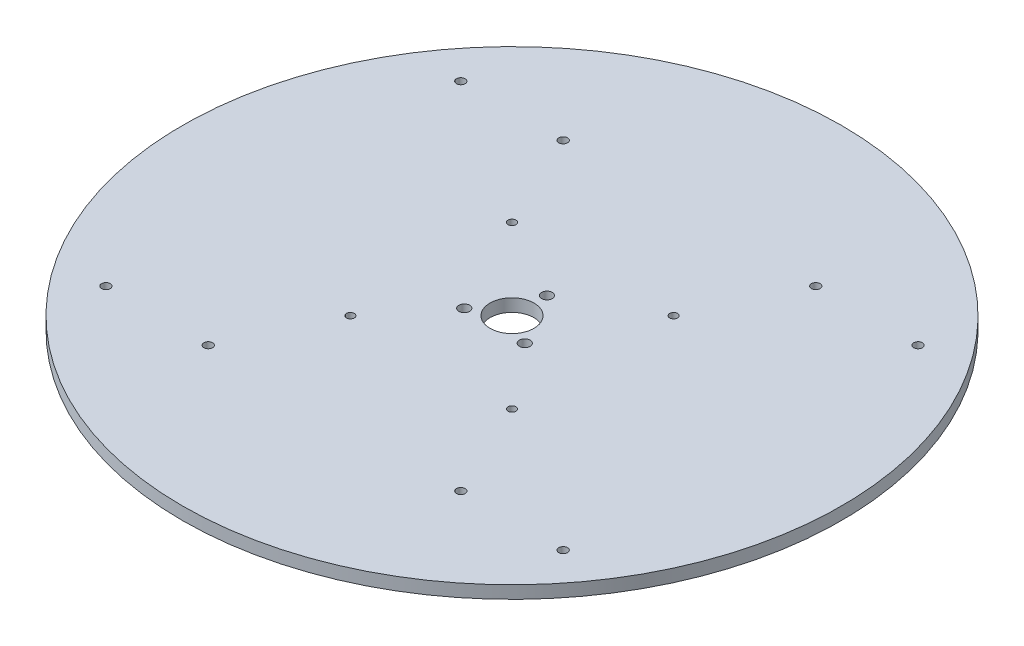
SolidWorks part; units mm, degrees
ref_plane "Front Plane" through (0, 0, 0) normal (0, 0, 1) x (1, 0, 0)
ref_plane "Top Plane" through (0, 0, 0) normal (0, 1, 0) x (1, 0, 0)
ref_plane "Right Plane" through (0, 0, 0) normal (1, 0, 0) x (0, 0, -1)
sketch "Sketch1" plane through (0, 0, 0) normal (0, 1, 0) x (1, 0, 0)
  circle A0 centre (0, 0) radius 165.1
  dimension "D1" = 330.2
extrude "Boss-Extrude1" add sketch "Sketch1" along normal blind 6.35
sketch "Sketch2" plane through (0, 6.35, 0) normal (0, 1, 0) x (1, 0, 0)
  line L0 (0, 0) -> (0, 17.5) construction
  line L1 (-40.4876, 40.4876) -> (40.4876, 40.4876) construction
  line L2 (-40.4876, 40.4876) -> (-40.4876, -40.4876) construction
  line L3 (-40.4876, -40.4876) -> (40.4876, -40.4876) construction
  line L4 (40.4876, 40.4876) -> (40.4876, -40.4876) construction
  line L5 (-40.4876, 40.4876) -> (40.4876, -40.4876) construction
  line L6 (-40.4876, -40.4876) -> (40.4876, 40.4876) construction
  line L7 (0, 0) -> (-15.1554, -8.75) construction
  line L8 (0, 0) -> (15.1554, -8.75) construction
  circle A0 centre (0, 0) radius 11
  circle A1 centre (-40.4876, 40.4876) radius 1.9844
  circle A2 centre (-40.4876, -40.4876) radius 1.9844
  circle A3 centre (40.4876, -40.4876) radius 1.9844
  circle A4 centre (40.4876, 40.4876) radius 1.9844
  circle A5 centre (0, 0) radius 17.5 construction
  circle A6 centre (0, 17.5) radius 2.7
  circle A7 centre (-15.1554, -8.75) radius 2.7
  circle A8 centre (15.1554, -8.75) radius 2.7
  dimension "D1" = 22
  dimension "D4" = 3.9688
  dimension "D5" = 35
  dimension "D8" = 5.4
  dimension "D2" = 80.9752
  dimension "D3" = 80.9752
  dimension "D6" = 120
  dimension "D7" = 120
extrude "Cut-Extrude1" cut sketch "Sketch2" against normal through all
sketch "Sketch3" plane through (0, 6.35, 0) normal (0, 1, 0) x (1, 0, 0)
  line L0 (-114.5413, 88.9) -> (-63.2587, 88.9) construction
  line L1 (-88.9, -88.9) -> (88.9, -88.9) construction
  line L2 (-88.9, -88.9) -> (-88.9, 88.9) construction
  line L3 (-88.9, 88.9) -> (88.9, 88.9) construction
  line L4 (88.9, -88.9) -> (88.9, 88.9) construction
  line L5 (-88.9, -88.9) -> (88.9, 88.9) construction
  line L6 (-88.9, 88.9) -> (88.9, -88.9) construction
  line L7 (-114.5413, -88.9) -> (-63.2587, -88.9) construction
  line L8 (114.5413, 88.9) -> (63.2587, 88.9) construction
  line L9 (114.5413, -88.9) -> (63.2587, -88.9) construction
  circle A0 centre (-114.5413, 88.9) radius 2.1828
  circle A1 centre (-63.2587, 88.9) radius 2.1828
  circle A2 centre (63.2587, 88.9) radius 2.1828
  circle A3 centre (114.5413, 88.9) radius 2.1828
  circle A4 centre (114.5413, -88.9) radius 2.1828
  circle A5 centre (63.2587, -88.9) radius 2.1828
  circle A6 centre (-63.2587, -88.9) radius 2.1828
  circle A7 centre (-114.5413, -88.9) radius 2.1828
  point P0 (0, 0)
  point P9 (-88.9, 88.9)
  point P12 (-88.9, -88.9)
  point P15 (88.9, 88.9)
  point P18 (88.9, -88.9)
  dimension "D1" = 4.3656
  dimension "D2" = 51.2826
  dimension "D3" = 177.8
  dimension "D4" = 177.8
extrude "Cut-Extrude2" cut sketch "Sketch3" against normal through all
